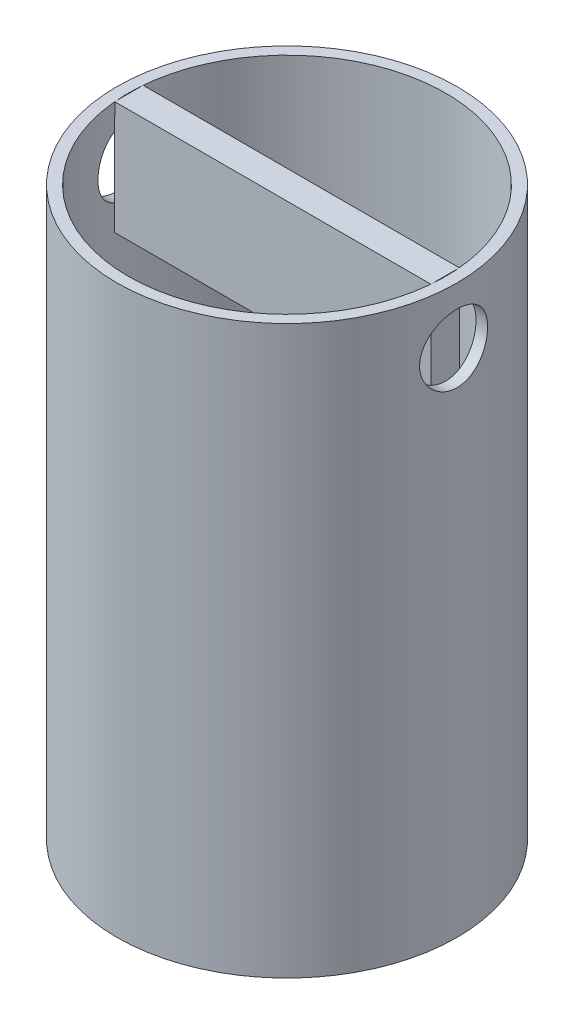
SolidWorks part; units mm, degrees
ref_plane "Front Plane" through (0, 0, 0) normal (0, 0, 1) x (1, 0, 0)
ref_plane "Top Plane" through (0, 0, 0) normal (0, 1, 0) x (1, 0, 0)
ref_plane "Right Plane" through (0, 0, 0) normal (1, 0, 0) x (0, 0, -1)
sketch "Sketch1" plane through (0, 0, 0) normal (0, 1, 0) x (1, 0, 0)
  circle A0 centre (0, 0) radius 14
  circle A1 centre (0, 0) radius 15
  dimension "D1" = 30
  dimension "D2" = 28
extrude "Boss-Extrude1" add sketch "Sketch1" along normal blind 50
sketch "Sketch2" plane through (0, 0, 0) normal (1, 0, 0) x (0, 0, -1)
  line L0 (14, 50) -> (-14, 50) construction
  circle A0 centre (0, 45) radius 3
  dimension "D1" = 5
extrude "Cut-Extrude1" cut sketch "Sketch2" against normal mid plane 30
sketch "Sketch3" plane through (0, 50, 0) normal (0, 1, 0) x (1, 0, 0)
  line L1 (13.9439, 1.2521) -> (-13.9439, 1.2521)
  line L2 (13.9439, 1.2521) -> (13.9439, -1.2521)
  line L3 (13.9439, -1.2521) -> (-13.9439, -1.2521)
  line L4 (-13.9439, 1.2521) -> (-13.9439, -1.2521)
  line L5 (13.9439, 1.2521) -> (-13.9439, -1.2521) construction
  line L6 (13.9439, -1.2521) -> (-13.9439, 1.2521) construction
  circle A0 centre (0, 0) radius 14 construction
  point P0 (0, 0)
extrude "Boss-Extrude2" add sketch "Sketch3" against normal blind 10 separate body
